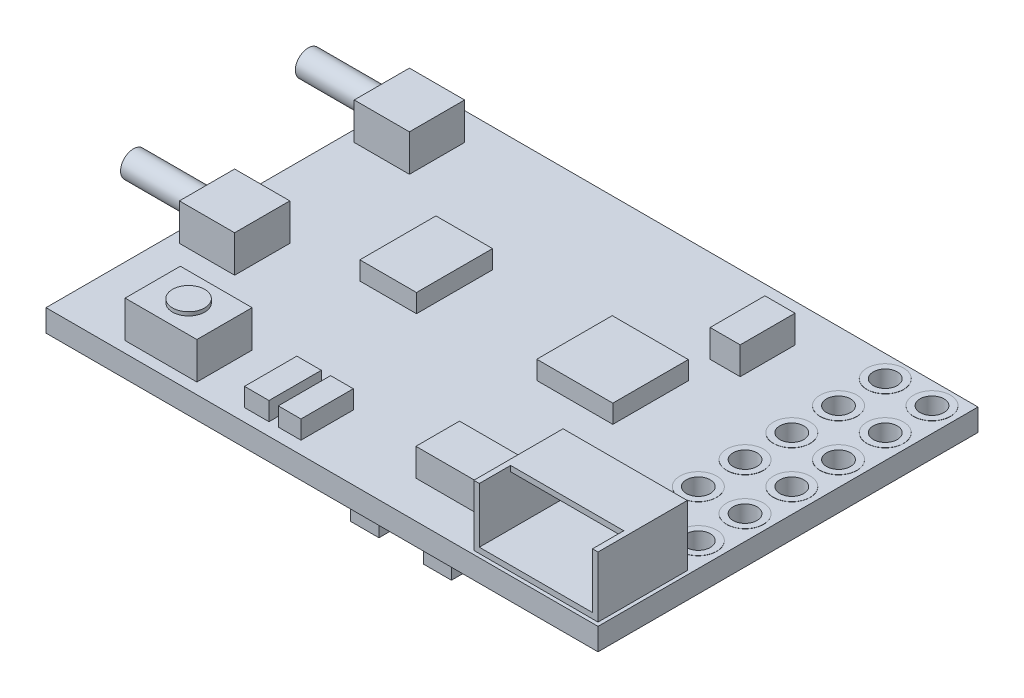
SolidWorks part; units mm, degrees
ref_plane "Front Plane" through (0, 0, 0) normal (0, 0, 1) x (1, 0, 0)
ref_plane "Top Plane" through (0, 0, 0) normal (0, 1, 0) x (1, 0, 0)
ref_plane "Right Plane" through (0, 0, 0) normal (1, 0, 0) x (0, 0, -1)
sketch "Sketch1" plane through (0, 0, 0) normal (0, 1, 0) x (1, 0, 0)
  line L1 (-15, 10.325) -> (15, 10.325)
  line L2 (-15, 10.325) -> (-15, -10.325)
  line L3 (-15, -10.325) -> (15, -10.325)
  line L4 (15, 10.325) -> (15, -10.325)
  line L5 (-15, 10.325) -> (15, -10.325) construction
  line L6 (-15, -10.325) -> (15, 10.325) construction
  point P0 (0, 0)
  dimension "D1" = 30
  dimension "D2" = 20.65
extrude "Boss-Extrude1" add sketch "Sketch1" along normal blind 1.2
sketch "Sketch2" plane through (0, 1.2, 0) normal (0, 1, 0) x (1, 0, 0)
  line L0 (13.7, 10.325) -> (13.7, -10.325) construction
  line L1 (15, 10.325) -> (-15, 10.325) construction
  line L2 (-15, -10.325) -> (15, -10.325) construction
  line L3 (11.16, 9.125) -> (13.7, 9.125) construction
  line L4 (15, -10.325) -> (15, 10.325) construction
  line L5 (13.7, 9.125) -> (13.7, 6.585) construction
  circle A0 centre (13.7, 9.125) radius 0.65
  circle A1 centre (11.16, 9.125) radius 0.65
  circle A2 centre (11.16, 6.585) radius 0.65
  circle A3 centre (11.16, 4.045) radius 0.65
  circle A4 centre (11.16, 1.505) radius 0.65
  circle A5 centre (11.16, -1.035) radius 0.65
  circle A6 centre (11.16, -3.575) radius 0.65
  circle A7 centre (13.7, 6.585) radius 0.65
  circle A8 centre (13.7, 4.045) radius 0.65
  circle A9 centre (13.7, 1.505) radius 0.65
  circle A10 centre (13.7, -1.035) radius 0.65
  circle A11 centre (13.7, -3.575) radius 0.65
  dimension "D3" = 1.3
  dimension "D1" = 1.3
  dimension "D2" = 2
  dimension "D4" = 1.2
  dimension "D6" = 2.54
  dimension "D5" = 6
extrude "Cut-Extrude1" cut sketch "Sketch2" against normal up to next
sketch "Sketch3" plane through (0, 1.2, 0) normal (0, 1, 0) x (1, 0, 0)
  line L0 (-15, -10.325) -> (15, -10.325) construction
  line L1 (14.8, -10.125) -> (8.05, -10.125)
  line L2 (14.8, -10.125) -> (14.8, -5.275)
  line L3 (14.8, -5.275) -> (8.05, -5.275)
  line L4 (8.05, -10.125) -> (8.05, -5.275)
  line L5 (15, -10.325) -> (15, 10.325) construction
  dimension "D1" = 6.75
  dimension "D2" = 4.85
  dimension "D3" = 0.2
  dimension "D4" = 0.2
extrude "Boss-Extrude2" add sketch "Sketch3" along normal blind 3.3
sketch "Sketch7" plane through (0, 4.5, 0) normal (0, 1, 0) x (1, 0, 0)
  line L0 (11.425, -5.275) -> (11.425, -10.125) construction
  line L1 (14.8, -5.275) -> (8.05, -5.275) construction
  line L2 (8.05, -10.125) -> (14.8, -10.125) construction
  line L3 (8.05, -10.125) -> (14.8, -10.125) construction
  line L4 (8.35, -10.125) -> (14.5, -10.125)
  line L5 (8.35, -10.125) -> (8.35, -8.425)
  line L6 (8.35, -8.425) -> (14.5, -8.425)
  line L7 (14.5, -10.125) -> (14.5, -8.425)
  line L8 (8.05, -5.275) -> (8.05, -10.125) construction
  point P12 (11.425, -8.425)
  dimension "D1" = 0.3
  dimension "D2" = 1.7
extrude "Cut-Extrude2" cut sketch "Sketch7" against normal offset from surface (3 mm away) 0.3 up to face at (11.16, 1.2, 4.225)
sketch "Sketch8" plane through (0, 0, 8.425) normal (0, 0, 1) x (1, 0, 0)
  line L0 (14.5, 1.5) -> (14.5, 4.5) construction
  line L1 (8.35, 1.5) -> (14.5, 1.5)
  line L2 (8.35, 1.5) -> (8.35, 4.2)
  line L3 (8.35, 4.2) -> (14.5, 4.2)
  line L4 (14.5, 1.5) -> (14.5, 4.2)
  line L5 (14.5, 4.5) -> (8.35, 4.5) construction
  dimension "D1" = 0.3
extrude "Cut-Extrude3" cut sketch "Sketch8" against normal offset from surface (2.85 mm away) 0.3 up to face at (11.425, 2.85, 5.275)
sketch "Sketch4" plane through (0, 1.2, 0) normal (0, 1, 0) x (1, 0, 0)
  line L1 (-14.4, 8.825) -> (-11.4, 8.825)
  line L2 (-14.4, 8.825) -> (-14.4, 5.825)
  line L3 (-14.4, 5.825) -> (-11.4, 5.825)
  line L4 (-11.4, 8.825) -> (-11.4, 5.825)
  line L5 (-15, 10.325) -> (-15, -10.325) construction
  line L6 (-15, 2.575) -> (15, 2.575) construction
  line L7 (15, -10.325) -> (15, 10.325) construction
  line L8 (-14.4, -0.675) -> (-11.4, -0.675)
  line L9 (-11.4, -3.675) -> (-11.4, -0.675)
  line L10 (-14.4, -3.675) -> (-11.4, -3.675)
  line L11 (-14.4, -3.675) -> (-14.4, -0.675)
  line L12 (-14.4, -2.175) -> (-11.4, -2.175) construction
  line L13 (-14.4, 7.325) -> (-11.4, 7.325) construction
  line L14 (15, 10.325) -> (-15, 10.325) construction
  dimension "D1" = 3
  dimension "D2" = 3
  dimension "D3" = 3
  dimension "D4" = 0.6
  dimension "D5" = 9.5
extrude "Boss-Extrude3" add sketch "Sketch4" along normal blind 2
sketch "Sketch5" plane through (0, 1.2, 0) normal (0, 1, 0) x (1, 0, 0)
  line L0 (-15, 10.325) -> (-15, -10.325) construction
  line L1 (-11.3, -9.725) -> (-7.4, -9.725)
  line L2 (-11.3, -9.725) -> (-11.3, -6.725)
  line L3 (-11.3, -6.725) -> (-7.4, -6.725)
  line L4 (-7.4, -9.725) -> (-7.4, -6.725)
  line L5 (-15, -10.325) -> (15, -10.325) construction
  dimension "D1" = 3.9
  dimension "D2" = 3
  dimension "D3" = 3.7
  dimension "D4" = 0.6
extrude "Boss-Extrude4" add sketch "Sketch5" along normal blind 2
sketch "Sketch6" plane through (0, 3.2, 0) normal (0, 1, 0) x (1, 0, 0)
  line L0 (-11.3, -8.225) -> (-7.4, -8.225) construction
  line L1 (-11.3, -6.725) -> (-11.3, -9.725) construction
  line L2 (-7.4, -9.725) -> (-7.4, -6.725) construction
  line L3 (-9.35, -6.725) -> (-9.35, -9.725) construction
  line L4 (-7.4, -6.725) -> (-11.3, -6.725) construction
  line L5 (-11.3, -9.725) -> (-7.4, -9.725) construction
  circle A0 centre (-9.35, -8.225) radius 0.875
  dimension "D1" = 1.75
extrude "Boss-Extrude5" add sketch "Sketch6" along normal blind 0.2
sketch "Sketch9" plane through (0, 1.2, 0) normal (0, 1, 0) x (1, 0, 0)
  line L1 (5.896, 3.685) -> (1.7624, 3.685)
  line L2 (5.896, 3.685) -> (5.896, -0.4166)
  line L3 (5.896, -0.4166) -> (1.7624, -0.4166)
  line L4 (1.7624, 3.685) -> (1.7624, -0.4166)
  line L5 (-7.7224, 3.5888) -> (-4.6463, 3.5888)
  line L6 (-7.7224, 3.5888) -> (-7.7224, -0.5447)
  line L7 (-7.7224, -0.5447) -> (-4.6463, -0.5447)
  line L8 (-4.6463, 3.5888) -> (-4.6463, -0.5447)
  line L9 (-4.9028, -6.7912) -> (-3.5716, -6.7912)
  line L10 (-4.9028, -6.7912) -> (-4.9028, -9.6355)
  line L11 (-4.9028, -9.6355) -> (-3.5716, -9.6355)
  line L12 (-3.5716, -6.7912) -> (-3.5716, -9.6355)
  line L13 (-4.9028, -6.7912) -> (-3.5716, -9.6355) construction
  line L14 (-4.9028, -9.6355) -> (-3.5716, -6.7912) construction
  line L15 (-3.066, -6.7912) -> (-1.833, -6.7912)
  line L16 (-3.066, -6.7912) -> (-3.066, -9.6355)
  line L17 (-3.066, -9.6355) -> (-1.833, -9.6355)
  line L18 (-1.833, -6.7912) -> (-1.833, -9.6355)
  line L19 (-3.066, -6.7912) -> (-1.833, -9.6355) construction
  line L20 (-3.066, -9.6355) -> (-1.833, -6.7912) construction
  point P12 (-4.2372, -8.2133)
  point P17 (-2.4495, -8.2133)
extrude "Boss-Extrude6" add sketch "Sketch9" along normal blind 1
sketch "Sketch10" plane through (0, 1.2, 0) normal (0, 1, 0) x (1, 0, 0)
  line L1 (7.1136, 8.2672) -> (5.4794, 8.2672)
  line L2 (7.1136, 8.2672) -> (7.1136, 5.2871)
  line L3 (7.1136, 5.2871) -> (5.4794, 5.2871)
  line L4 (5.4794, 8.2672) -> (5.4794, 5.2871)
  line L5 (7.5302, -5.928) -> (3.0762, -5.928)
  line L6 (7.5302, -5.928) -> (7.5302, -8.2992)
  line L7 (7.5302, -8.2992) -> (3.0762, -8.2992)
  line L8 (3.0762, -5.928) -> (3.0762, -8.2992)
extrude "Boss-Extrude7" add sketch "Sketch10" along normal blind 1.5
sketch "Sketch11" plane through (0, 0, 0) normal (0, -1, 0) x (1, 0, 0)
  line L1 (-6.3538, 2.621) -> (0.4959, 2.621)
  line L2 (-6.3538, 2.621) -> (-6.3538, -4.2287)
  line L3 (-6.3538, -4.2287) -> (0.4959, -4.2287)
  line L4 (0.4959, 2.621) -> (0.4959, -4.2287)
  line L6 (-15, -10.325) -> (-15, 10.325) construction
  line L7 (6.1467, 9.4396) -> (4.628, 9.4396)
  line L8 (6.1467, 9.4396) -> (6.1467, 6.4332)
  line L9 (6.1467, 6.4332) -> (4.628, 6.4332)
  line L10 (4.628, 9.4396) -> (4.628, 6.4332)
  line L11 (2.1795, 9.4086) -> (0.6298, 9.4086)
  line L12 (2.1795, 9.4086) -> (2.1795, 6.3402)
  line L13 (2.1795, 6.3402) -> (0.6298, 6.3402)
  line L14 (0.6298, 9.4086) -> (0.6298, 6.3402)
  line L15 (4.9689, 5.6274) -> (6.1467, 5.6274)
  line L16 (4.9689, 5.6274) -> (4.9689, 2.8689)
  line L17 (4.9689, 2.8689) -> (6.1467, 2.8689)
  line L18 (6.1467, 5.6274) -> (6.1467, 2.8689)
  line L19 (-15, -4.3837) -> (-12.1398, -4.3837)
  line L20 (-15, -4.3837) -> (-15, -8.5679)
  line L21 (-15, -8.5679) -> (-12.1398, -8.5679)
  line L22 (-12.1398, -4.3837) -> (-12.1398, -8.5679)
  line L23 (-13.5965, 3.7987) -> (-11.21, 3.7987)
  line L24 (-13.5965, 3.7987) -> (-13.5965, 0.6993)
  line L25 (-13.5965, 0.6993) -> (-11.21, 0.6993)
  line L26 (-11.21, 3.7987) -> (-11.21, 0.6993)
  line L27 (-10.0012, -6.3053) -> (-8.7304, -6.3053)
  line L28 (-10.0012, -6.3053) -> (-10.0012, -9.4667)
  line L29 (-10.0012, -9.4667) -> (-8.7304, -9.4667)
  line L30 (-8.7304, -6.3053) -> (-8.7304, -9.4667)
extrude "Boss-Extrude8" add sketch "Sketch11" along normal blind 1.5
sketch "Sketch12" plane through (0, 1.2, 0) normal (0, 1, 0) x (1, 0, 0)
  circle A0 centre (11.16, 9.125) radius 1
  circle A1 centre (13.7, 9.125) radius 1
  circle A2 centre (13.7, 6.585) radius 1
  circle A3 centre (11.16, 6.585) radius 1
  circle A4 centre (11.16, 4.045) radius 1
  circle A5 centre (13.7, 4.045) radius 1
  circle A6 centre (13.7, 1.505) radius 1
  circle A7 centre (11.16, 1.505) radius 1
  circle A8 centre (11.16, -1.035) radius 1
  circle A9 centre (11.16, -3.575) radius 1
  circle A10 centre (13.7, -3.575) radius 1
  circle A11 centre (13.7, -1.035) radius 1
  circle A12 centre (11.16, -3.575) radius 0.65 construction
  circle A13 centre (13.7, -3.575) radius 0.65 construction
  circle A14 centre (13.7, -1.035) radius 0.65 construction
  circle A15 centre (11.16, -1.035) radius 0.65 construction
  circle A16 centre (11.16, 1.505) radius 0.65 construction
  circle A17 centre (13.7, 1.505) radius 0.65 construction
  circle A18 centre (13.7, 4.045) radius 0.65 construction
  circle A19 centre (11.16, 4.045) radius 0.65 construction
  circle A20 centre (11.16, 6.585) radius 0.65 construction
  circle A21 centre (13.7, 6.585) radius 0.65 construction
  circle A22 centre (13.7, 9.125) radius 0.65 construction
  circle A23 centre (11.16, 9.125) radius 0.65 construction
  circle A24 centre (11.16, -3.575) radius 0.65
  circle A25 centre (13.7, -3.575) radius 0.65
  circle A26 centre (13.7, -1.035) radius 0.65
  circle A27 centre (11.16, -1.035) radius 0.65
  circle A28 centre (11.16, 1.505) radius 0.65
  circle A29 centre (13.7, 1.505) radius 0.65
  circle A30 centre (13.7, 4.045) radius 0.65
  circle A31 centre (11.16, 4.045) radius 0.65
  circle A32 centre (11.16, 6.585) radius 0.65
  circle A33 centre (13.7, 6.585) radius 0.65
  circle A34 centre (13.7, 9.125) radius 0.65
  circle A35 centre (11.16, 9.125) radius 0.65
  dimension "D1" = 2
extrude "Boss-Extrude9" add sketch "Sketch12" along normal blind 0.01
ref_plane "Plane1" through (0, 0.6, 0) normal (0, 1, 0) x (1, 0, 0)
mirror "Mirror1" about plane through (0, 0.6, 0) normal (0, 1, 0) of "Boss-Extrude9"
sketch "Sketch13" plane through (-14.4, 0, 0) normal (-1, 0, 0) x (0, 0, 1)
  line L0 (-8.825, 1.2) -> (-5.825, 3.2) construction
  line L1 (0.675, 1.2) -> (3.675, 3.2) construction
  circle A0 centre (-7.325, 2.2) radius 0.7
  circle A1 centre (2.175, 2.2) radius 0.7
  dimension "D1" = 1.4
extrude "Boss-Extrude10" add sketch "Sketch13" along normal blind 4
